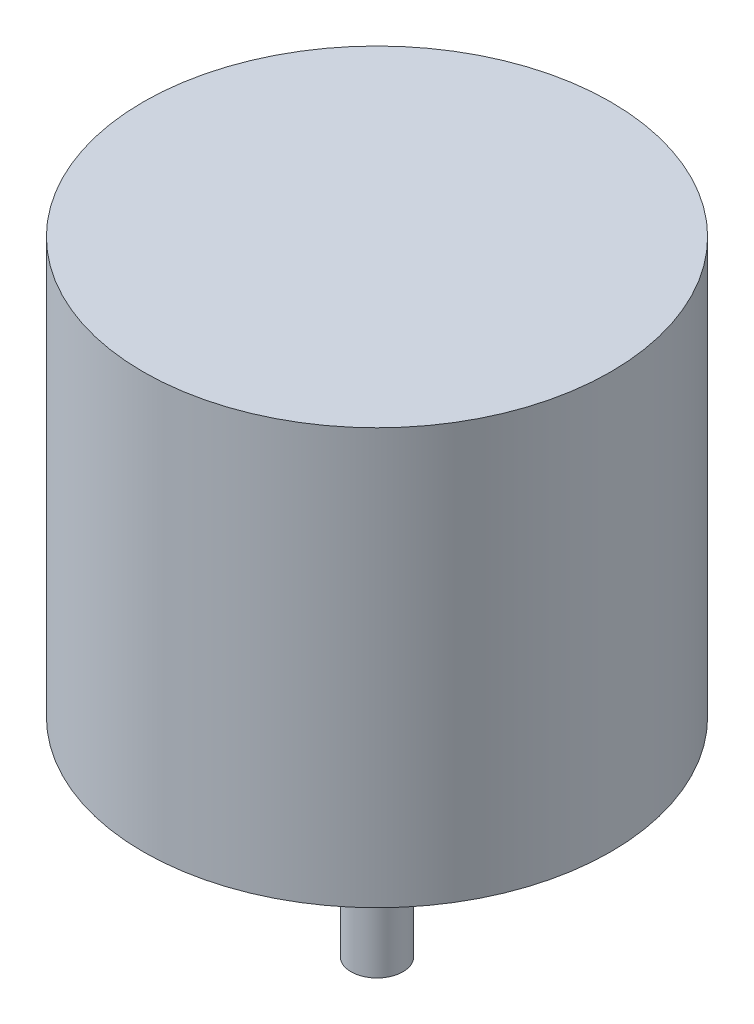
SolidWorks part; units mm, degrees
ref_plane "Front Plane" through (0, 0, 0) normal (0, 0, 1) x (1, 0, 0)
ref_plane "Top Plane" through (0, 0, 0) normal (0, 1, 0) x (1, 0, 0)
ref_plane "Right Plane" through (0, 0, 0) normal (1, 0, 0) x (0, 0, -1)
sketch "Sketch1" plane through (0, 0, 0) normal (0, 1, 0) x (1, 0, 0)
  circle A0 centre (0, 0) radius 28.575
  dimension "D1" = 57.15
extrude "Boss-Extrude1" add sketch "Sketch1" along normal blind 50.8
sketch "Sketch2" plane through (0, 0, 0) normal (0, -1, 0) x (1, 0, 0)
  circle A0 centre (0, 0) radius 3.175
  dimension "D1" = 6.35
extrude "Boss-Extrude2" add sketch "Sketch2" along normal blind 25.4
